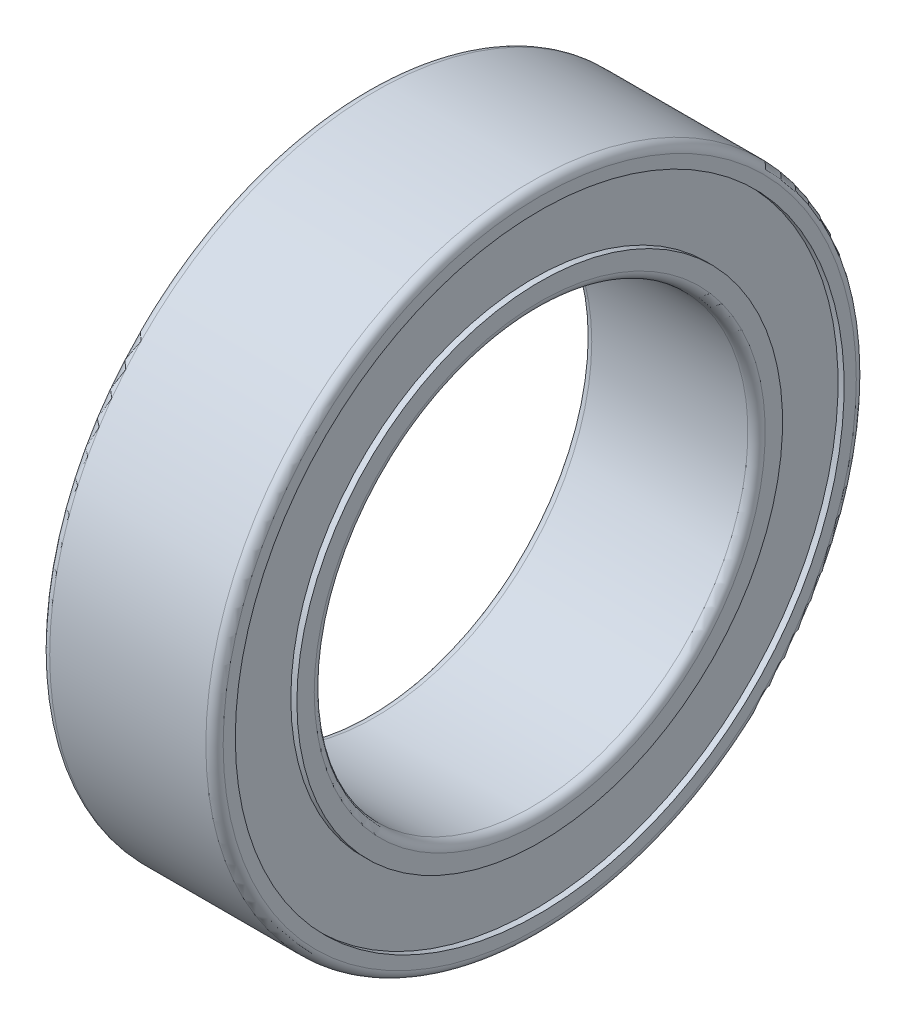
SolidWorks part; units mm, degrees
ref_plane "Front Plane" through (0, 0, 0) normal (0, 0, 1) x (1, 0, 0)
ref_plane "Top Plane" through (0, 0, 0) normal (0, 1, 0) x (1, 0, 0)
ref_plane "Right Plane" through (0, 0, 0) normal (1, 0, 0) x (0, 0, -1)
sketch "Sketch1" plane through (0, 0, 0) normal (0, 0, 1) x (1, 0, 0)
  line L0 (0, 0) -> (4, 0) construction
  line L1 (0, 5) -> (4, 5)
  line L2 (0, 7.5) -> (4, 7.5)
  line L3 (0, 7.5) -> (0, 7.02)
  line L4 (0, 7.02) -> (0.14, 7.02)
  line L5 (4, 7.5) -> (4, 7.02)
  line L6 (0.14, 7.02) -> (0.14, 5.6)
  line L7 (0.14, 5.6) -> (0, 5.6)
  line L8 (0, 5.6) -> (0, 5)
  line L9 (4, 7.02) -> (3.86, 7.02)
  line L10 (3.86, 7.02) -> (3.86, 5.6)
  line L11 (3.86, 5.6) -> (4, 5.6)
  line L12 (4, 5.6) -> (4, 5)
  dimension "D" = 15
  dimension "B" = 4
  dimension "D_s" = 10
  dimension "MSM_1" = 14.04
  dimension "MSM_2" = 11.2
  dimension "MSM_3" = 0.14
revolve "Revolve1" add sketch "Sketch1" angle 360 about L0
fillet "Fillet1" radius 0.2 2 edges at (4, 0, 7.5) (0, 0, 7.5)
fillet "Fillet2" radius 0.2 2 edges at (4, 0, 5) (0, 0, 5)
